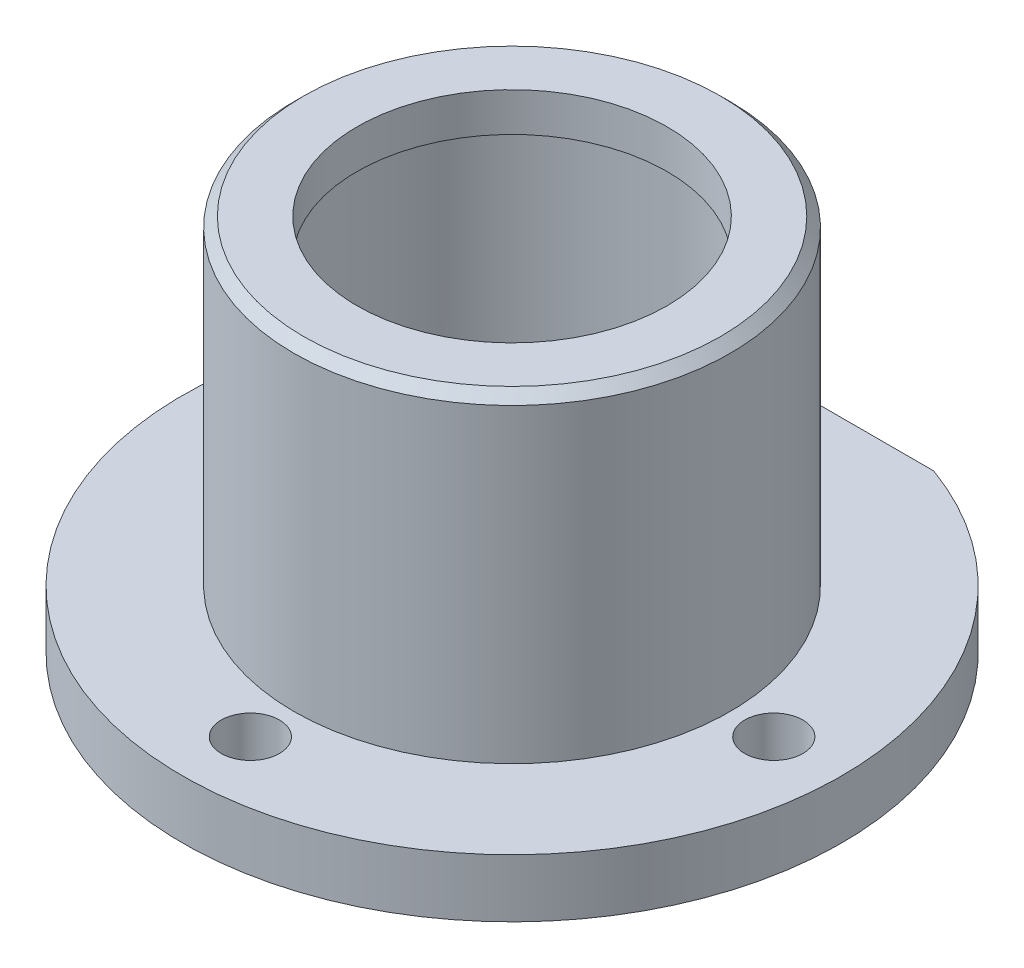
SolidWorks part; units mm, degrees
ref_plane "前视基准面" through (0, 0, 0) normal (0, 0, 1) x (1, 0, 0)
ref_plane "上视基准面" through (0, 0, 0) normal (0, 1, 0) x (1, 0, 0)
ref_plane "右视基准面" through (0, 0, 0) normal (1, 0, 0) x (0, 0, -1)
other "Configuration Table"
sketch "草图1" plane through (0, 0, 0) normal (0, 1, 0) x (1, 0, 0)
  line L0 (11.4891, 32) -> (-11.4891, 32)
  arc A0 (-11.4891, 32) -> (11.4891, 32) centre (0, 0) ccw
  circle A1 centre (0, 0) radius 27 construction
  circle A2 centre (0, 27) radius 3
  circle A3 centre (27, 0) radius 3
  circle A4 centre (0, -27) radius 3
  circle A5 centre (-27, 0) radius 3
  point P7 (-27, 0)
  point P16 (0, 0)
  dimension "D1" = 68
  dimension "D3" = 54
  dimension "D4" = 6
  dimension "D2" = 32
  dimension "D5" = 4
extrude "凸台-拉伸1" add sketch "草图1" along normal blind 6
sketch "草图2" plane through (0, 6, 0) normal (0, 1, 0) x (1, 0, 0)
  circle A0 centre (0, 0) radius 22.5
  dimension "D1" = 45
extrude "凸台-拉伸2" add sketch "草图2" along normal offset from surface (33 mm away) 39 up to face at (0, 0, 1)
sketch "草图3" plane through (0, 0, 0) normal (0, 0, 1) x (1, 0, 0)
  line L0 (0, 0) -> (0, 39) construction
  line L1 (22.5, 39) -> (-22.5, 39) construction
  line L2 (0, 39) -> (16, 39)
  line L3 (16, 39) -> (16, 35)
  line L4 (16, 35) -> (18.5, 35)
  line L5 (18.5, 35) -> (18.5, 0)
  line L6 (-34, 0) -> (34, 0) construction
  line L7 (18.5, 0) -> (0, 0)
  line L8 (0, 0) -> (0, 39)
  dimension "D1" = 32
  dimension "D2" = 37
  dimension "D3" = 4
revolve "切除-旋转1" cut sketch "草图3" angle 360 about L0
chamfer "倒角1" distance 1 angle 45 2 edges at (0, 39, 22.5) (18.5, 0, 0)
